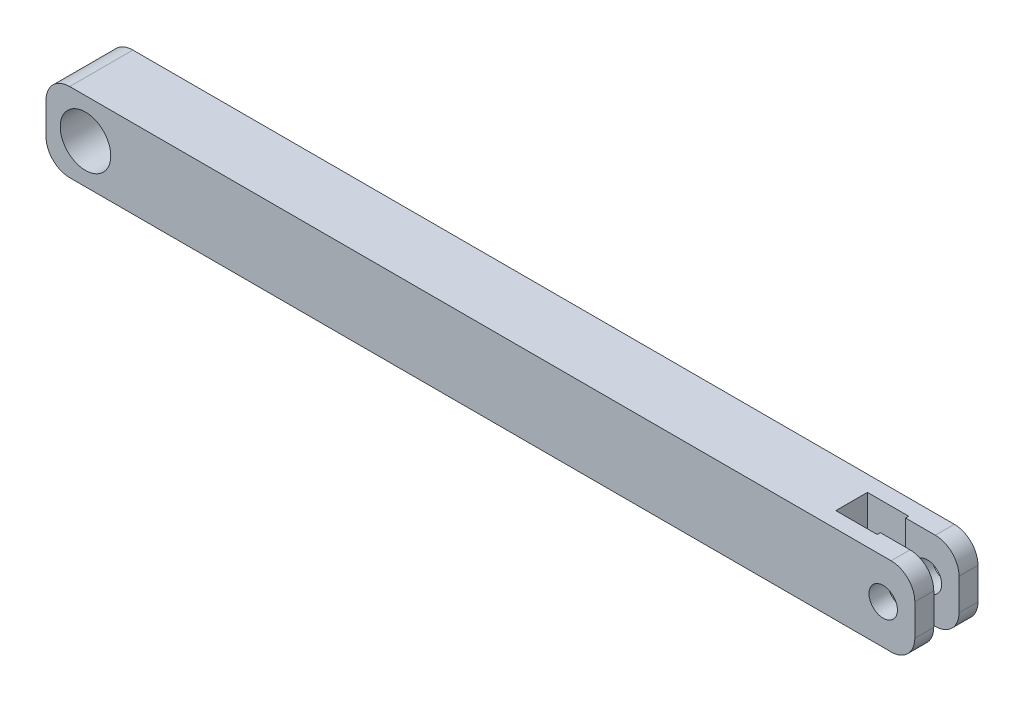
SolidWorks part; units mm, degrees
ref_plane "前视基准面" through (0, 0, 0) normal (0, 0, 1) x (1, 0, 0)
ref_plane "上视基准面" through (0, 0, 0) normal (0, 1, 0) x (1, 0, 0)
ref_plane "右视基准面" through (0, 0, 0) normal (1, 0, 0) x (0, 0, -1)
other "Configuration Table"
sketch "草图5" plane through (0, 0, 0) normal (0, 1, 0) x (1, 0, 0)
  line L0 (0, 0) -> (0, -3)
  line L4 (55, -3) -> (55, 0)
  line L8 (55, 0) -> (0, 0)
  line L9 (0, -3) -> (55, -3)
  dimension "D6" = 3
  dimension "D1" = 55
  dimension "D5" = 3
extrude "凸台-拉伸1" add sketch "草图5" along normal blind 5
sketch "草图6" plane through (0, 0, 3) normal (0, 0, 1) x (1, 0, 0)
  line L2 (0, 5) -> (0, 0) construction
  line L3 (0, 5) -> (55, 5) construction
  circle A0 centre (2.5, 2.5) radius 1.6
  dimension "D1" = 3.2
  dimension "D2" = 2.5
  dimension "D3" = 2.5
extrude "切除-拉伸1" cut sketch "草图6" against normal up to next
sketch "草图7" plane through (0, 0, 0) normal (0, 0, 1) x (1, 0, 0)
  line L0 (55, 5) -> (55, 0) construction
  circle A0 centre (53, 2.5) radius 0.9
  point P6 (55, 2.5)
  dimension "D1" = 1.8
  dimension "D2" = 2
extrude "切除-拉伸2" cut sketch "草图7" along normal up to next
fillet "圆角1" radius 1.5 4 edges at (55, 5, 1.5) (55, 0, 1.5) (0, 0, 1.5) (0, 5, 1.5)
sketch "草图8" plane through (0, 5, 0) normal (0, 1, 0) x (1, 0, 0)
  line L0 (55, 0) -> (55, -3) construction
  line L1 (55, -0.7) -> (49, -0.7)
  line L2 (55, -0.7) -> (55, -2.3)
  line L3 (55, -2.3) -> (49, -2.3)
  line L4 (49, -0.7) -> (49, -2.3)
  point P6 (55, -1.5)
  dimension "D1" = 1.6
  dimension "D2" = 6
extrude "切除-拉伸3" cut sketch "草图8" against normal blind 10
sketch "草图9" plane through (0, 0, 0) normal (0, -1, 0) x (1, 0, 0)
  line L1 (54, 0.5) -> (58.5, 0.5)
  line L2 (49, 0.5) -> (49, 2.5)
  line L3 (49, 2.5) -> (53.5, 2.5)
  line L4 (53.5, 0.5) -> (53.5, 2.5)
  line L5 (49, 0.5) -> (51.6166, 0.5)
  line L6 (49, 0.5) -> (49, 2.5)
  line L7 (49, 2.5) -> (51.6166, 2.5)
  line L8 (49, 0.7) -> (49, 2.3)
  line L9 (49, 2.3) -> (53.5, 2.3)
  line L10 (53.5, 2.3) -> (53.5, 3)
  line L11 (53.5, 3) -> (1.5, 3)
  line L12 (1.5, 3) -> (1.5, 0)
  line L13 (1.5, 0) -> (53.5, 0)
  line L14 (53.5, 0) -> (53.5, 0.7)
  line L15 (53.5, 0.7) -> (49, 0.7)
  line L16 (49, 0.7) -> (49, 2.3)
  line L17 (49, 2.3) -> (53.5, 2.3)
  line L18 (53.5, 2.3) -> (53.5, 3)
  line L19 (53.5, 3) -> (1.5, 3)
  line L20 (1.5, 3) -> (1.5, 0)
  line L21 (1.5, 0) -> (53.5, 0)
  line L22 (53.5, 0) -> (53.5, 0.7)
  line L23 (53.5, 0.7) -> (49, 0.7)
  line L24 (51.6166, 0.5) -> (51.6166, 2.5)
  line M12 (49, 0.7) -> (49, 2.3)
  line M13 (49, 2.3) -> (53.5, 2.3)
  line M14 (53.5, 2.3) -> (53.5, 3)
  line M18 (53.5, 0) -> (53.5, 0.7)
  line M19 (53.5, 0.7) -> (49, 0.7)
  dimension "D2" = 0.2
  dimension "D3" = 0.2
  dimension "D1" = 0
extrude "切除-拉伸4" cut sketch "草图9" against normal blind 10 contours L1 L24 L7 L4 M14 M18 | L4 M19 M13 M12 | L2 L1 M18 M19 | L3 L2 M13 M14
sketch "草图10" plane through (0, 0, 3) normal (0, 0, 1) x (1, 0, 0)
  line L4 (55, 1.5) -> (55, 3.5)
  line L5 (53.5, 5) -> (1.5, 5)
  line L6 (0, 3.5) -> (0, 1.5)
  line L7 (1.5, 0) -> (53.5, 0)
  line L8 (55, 1.5) -> (55, 3.5)
  line L9 (53.5, 5) -> (1.5, 5)
  line L10 (0, 3.5) -> (0, 1.5)
  line L11 (1.5, 0) -> (53.5, 0)
  circle A0 centre (2.5, 2.5) radius 1.6 construction
  circle A1 centre (2.5, 2.5) radius 1.6
  circle A2 centre (53, 2.5) radius 0.9 construction
  circle A3 centre (53, 2.5) radius 0.9
  arc A4 (55, 3.5) -> (53.5, 5) centre (53.5, 3.5) ccw
  arc A5 (1.5, 5) -> (0, 3.5) centre (1.5, 3.5) ccw
  arc A6 (0, 1.5) -> (1.5, 0) centre (1.5, 1.5) ccw
  arc A7 (53.5, 0) -> (55, 1.5) centre (53.5, 1.5) ccw
  arc A8 (55, 3.5) -> (53.5, 5) centre (53.5, 3.5) ccw
  arc A9 (1.5, 5) -> (0, 3.5) centre (1.5, 3.5) ccw
  arc A10 (0, 1.5) -> (1.5, 0) centre (1.5, 1.5) ccw
  arc A11 (53.5, 0) -> (55, 1.5) centre (53.5, 1.5) ccw
  dimension "D1" = 0
extrude "凸台-拉伸2" add sketch "草图10" along normal blind 0.5
sketch "草图11" plane through (0, 0, 0) normal (0, 0, -1) x (-1, 0, 0)
  line L4 (-1.5, 5) -> (-53.5, 5)
  line L5 (-55, 3.5) -> (-55, 1.5)
  line L6 (-53.5, 0) -> (-1.5, 0)
  line L7 (0, 1.5) -> (0, 3.5)
  line L8 (-1.5, 5) -> (-53.5, 5)
  line L9 (-55, 3.5) -> (-55, 1.5)
  line L10 (-53.5, 0) -> (-1.5, 0)
  line L11 (0, 1.5) -> (0, 3.5)
  circle A0 centre (-53, 2.5) radius 0.9 construction
  circle A1 centre (-2.5, 2.5) radius 1.6 construction
  circle A2 centre (-53, 2.5) radius 0.9
  circle A3 centre (-2.5, 2.5) radius 1.6
  arc A4 (-53.5, 5) -> (-55, 3.5) centre (-53.5, 3.5) ccw
  arc A5 (-55, 1.5) -> (-53.5, 0) centre (-53.5, 1.5) ccw
  arc A6 (-1.5, 0) -> (0, 1.5) centre (-1.5, 1.5) ccw
  arc A7 (0, 3.5) -> (-1.5, 5) centre (-1.5, 3.5) ccw
  arc A8 (-53.5, 5) -> (-55, 3.5) centre (-53.5, 3.5) ccw
  arc A9 (-55, 1.5) -> (-53.5, 0) centre (-53.5, 1.5) ccw
  arc A10 (-1.5, 0) -> (0, 1.5) centre (-1.5, 1.5) ccw
  arc A11 (0, 3.5) -> (-1.5, 5) centre (-1.5, 3.5) ccw
  dimension "D1" = 0
extrude "凸台-拉伸3" add sketch "草图11" along normal blind 0.5
